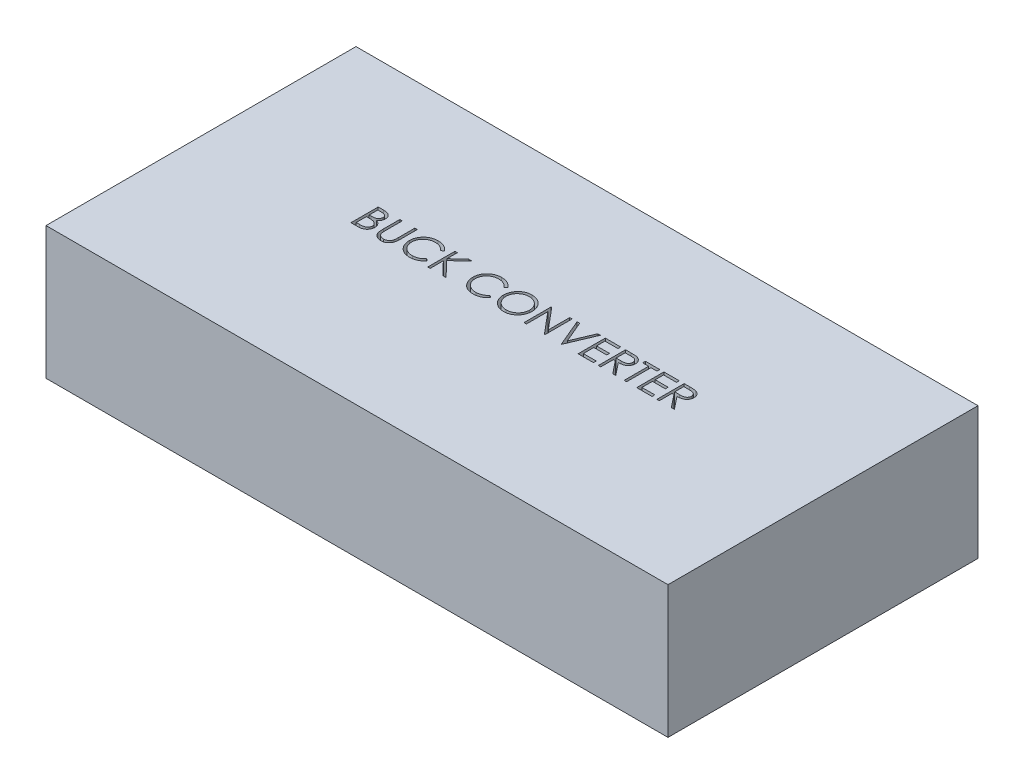
SolidWorks part; units mm, degrees
ref_plane "Front Plane" through (0, 0, 0) normal (0, 0, 1) x (1, 0, 0)
ref_plane "Top Plane" through (0, 0, 0) normal (0, 1, 0) x (1, 0, 0)
ref_plane "Right Plane" through (0, 0, 0) normal (1, 0, 0) x (0, 0, -1)
sketch "Sketch1" plane through (0, 0, 0) normal (0, 1, 0) x (1, 0, 0)
  line L1 (-40.005, -19.939) -> (40.005, -19.939)
  line L2 (-40.005, -19.939) -> (-40.005, 19.939)
  line L3 (-40.005, 19.939) -> (40.005, 19.939)
  line L4 (40.005, -19.939) -> (40.005, 19.939)
  line L5 (-40.005, -19.939) -> (40.005, 19.939) construction
  line L6 (-40.005, 19.939) -> (40.005, -19.939) construction
  point P0 (0, 0)
  dimension "D1" = 80.01
  dimension "D2" = 39.878
extrude "Boss-Extrude1" add sketch "Sketch1" along normal blind 17.018
sketch "Sketch4" plane through (0, 17.018, 0) normal (0, 1, 0) x (1, 0, 0)
  line L0 (-40.005, 0) -> (40.005, 0) construction
  line L2 (40.005, -19.939) -> (40.005, 19.939) construction
  text T0 "BUCK CONVERTER"
  point P3 (0, 0)
extrude "Cut-Extrude2" cut sketch "Sketch4" against normal blind 12.7
